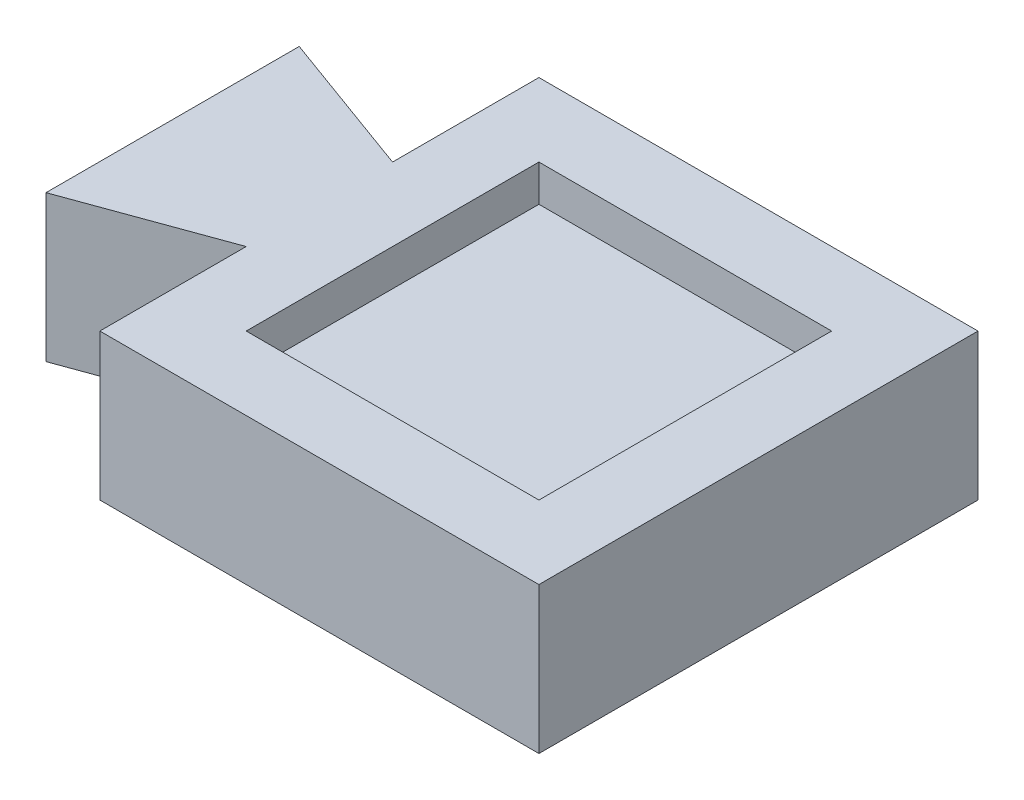
SolidWorks part; units mm, degrees
ref_plane "Front Plane" through (0, 0, 0) normal (0, 0, 1) x (1, 0, 0)
ref_plane "Top Plane" through (0, 0, 0) normal (0, 1, 0) x (1, 0, 0)
ref_plane "Right Plane" through (0, 0, 0) normal (1, 0, 0) x (0, 0, -1)
sketch "Sketch1" plane through (0, 0, 0) normal (0, 1, 0) x (1, 0, 0)
  line L0 (0, -25.4) -> (-25.4719, -16.129)
  line L1 (-25.4719, -16.129) -> (-25.4719, -60.071)
  line L2 (-25.4719, -60.071) -> (0, -50.8)
  line L3 (0, -50.8) -> (0, -76.2)
  line L4 (0, -76.2) -> (76.2, -76.2)
  line L5 (76.2, -76.2) -> (76.2, 0)
  line L6 (76.2, 0) -> (0, 0)
  line L7 (0, 0) -> (0, -25.4)
  dimension "D1" = 76.2
  dimension "D2" = 25.4
  dimension "D3" = 110
  dimension "D4" = 43.942
extrude "Boss-Extrude1" add sketch "Sketch1" along normal blind 25.4
sketch "Sketch2" plane through (0, 25.4, 0) normal (0, 1, 0) x (1, 0, 0)
  line L0 (0, -76.2) -> (76.2, 0) construction
  line L1 (12.7, -12.7) -> (63.5, -12.7)
  line L2 (12.7, -12.7) -> (12.7, -63.5)
  line L3 (12.7, -63.5) -> (63.5, -63.5)
  line L4 (63.5, -12.7) -> (63.5, -63.5)
  line L5 (12.7, -12.7) -> (63.5, -63.5) construction
  line L6 (12.7, -63.5) -> (63.5, -12.7) construction
  point P0 (38.1, -38.1)
  point P9 (38.1, -38.1)
  dimension "D1" = 50.8
extrude "Cut-Extrude1" cut sketch "Sketch2" against normal blind 6.35
